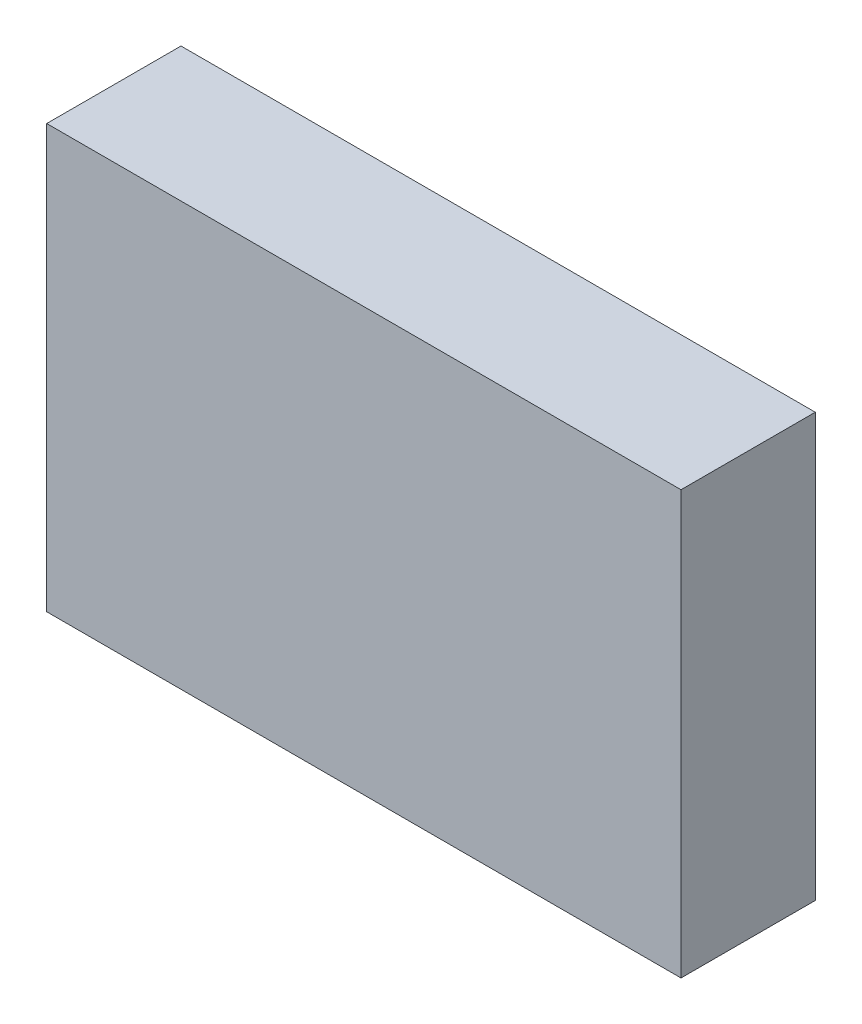
SolidWorks part; units mm, degrees
ref_plane "Front Plane" through (0, 0, 0) normal (0, 0, 1) x (1, 0, 0)
ref_plane "Top Plane" through (0, 0, 0) normal (0, 1, 0) x (1, 0, 0)
ref_plane "Right Plane" through (0, 0, 0) normal (1, 0, 0) x (0, 0, -1)
sketch "Sketch1" plane through (0, 0, 0) normal (0, 0, 1) x (1, 0, 0)
  line L1 (60, -40) -> (-60, -40)
  line L2 (60, -40) -> (60, 40)
  line L3 (60, 40) -> (-60, 40)
  line L4 (-60, -40) -> (-60, 40)
  line L5 (60, -40) -> (-60, 40) construction
  line L6 (60, 40) -> (-60, -40) construction
  point P0 (0, 0)
  dimension "D1" = 120
  dimension "D2" = 80
extrude "Boss-Extrude1" add sketch "Sketch1" along normal blind 25.4
